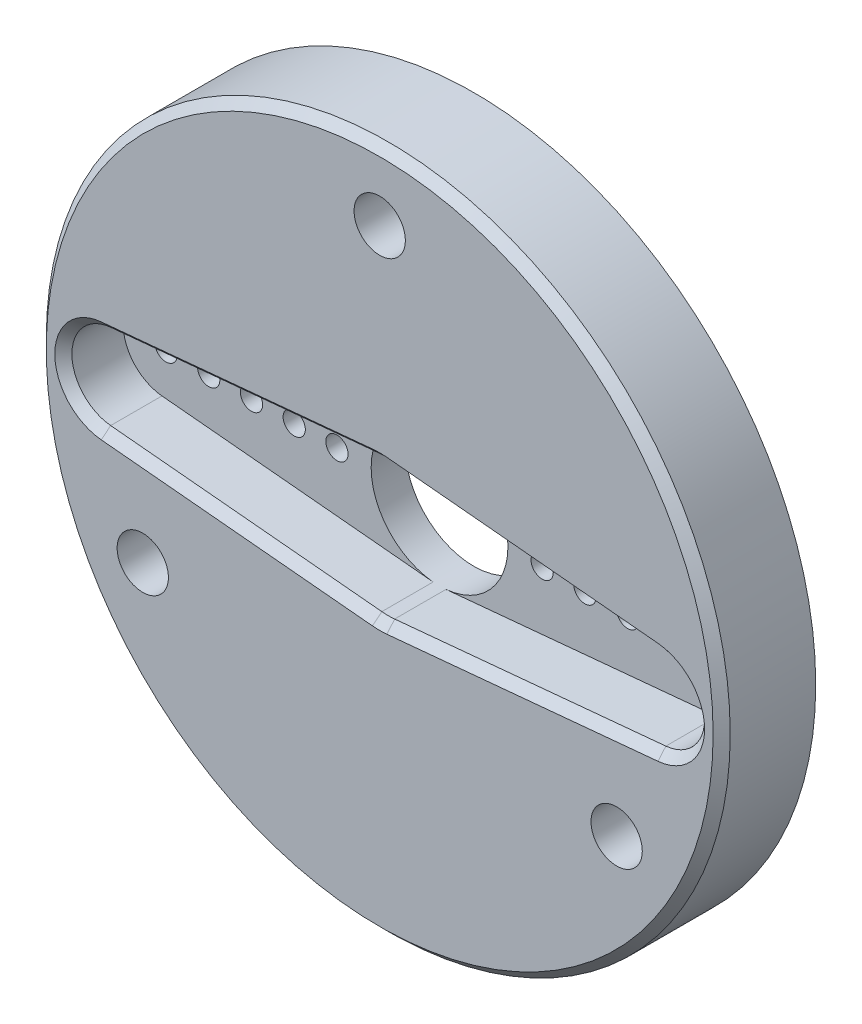
SolidWorks part; units mm, degrees
ref_plane "前视基准面" through (0, 0, 0) normal (0, 0, 1) x (1, 0, 0)
ref_plane "上视基准面" through (0, 0, 0) normal (0, 1, 0) x (1, 0, 0)
ref_plane "右视基准面" through (0, 0, 0) normal (1, 0, 0) x (0, 0, -1)
sketch "草图1" plane through (0, 0, 0) normal (0, 0, 1) x (1, 0, 0)
  line L0 (0, -3.025) -> (0, 3.025) construction
  circle A0 centre (0, 0) radius 20
  circle A1 centre (0, 0) radius 4
  circle A2 centre (6, 0) radius 0.65
  circle A3 centre (8.5, 0) radius 0.65
  circle A4 centre (11, 0) radius 0.65
  circle A5 centre (13.5, 0) radius 0.65
  circle A6 centre (16, 0) radius 0.65
  circle A7 centre (-16, 0) radius 0.65
  circle A8 centre (-13.5, 0) radius 0.65
  circle A9 centre (-11, 0) radius 0.65
  circle A10 centre (-8.5, 0) radius 0.65
  circle A11 centre (-6, 0) radius 0.65
  dimension "D1" = 40
  dimension "D2" = 8
  dimension "D4" = 1.3
  dimension "D3" = 6
  dimension "D6" = 10
  dimension "D5" = 5
extrude "凸台-拉伸1" add sketch "草图1" along normal blind 5.5
sketch "草图2" plane through (0, 0, 5.5) normal (0, 0, 1) x (1, 0, 0)
  line L0 (-16.2344, 2.489) -> (-0.375, 3.9824)
  line L1 (3.025, 0) -> (-3.025, 0) construction
  line L2 (-16.2344, -2.489) -> (-0.375, -3.9824)
  line L3 (0, -3.025) -> (0, 3.025) construction
  line L4 (16.2344, -2.489) -> (0.375, -3.9824)
  line L5 (16.2344, 2.489) -> (0.375, 3.9824)
  arc A0 (-16.2344, 2.489) -> (-16.2344, -2.489) centre (-16, 0) ccw
  circle A1 centre (0, 0) radius 4 construction
  arc A2 (-0.375, -3.9824) -> (0.375, -3.9824) centre (0, 0) ccw
  arc A3 (16.2344, 2.489) -> (16.2344, -2.489) centre (16, 0) cw
  arc A4 (0.375, 3.9824) -> (-0.375, 3.9824) centre (0, 0) ccw
  dimension "D1" = 5
extrude "切除-拉伸1" cut sketch "草图2" against normal blind 3.5
sketch "草图3" plane through (0, 0, 5.5) normal (0, 0, 1) x (1, 0, 0)
  circle A0 centre (0, 16) radius 1.5
  circle A1 centre (13.8564, -8) radius 1.5
  circle A2 centre (-13.8564, -8) radius 1.5
  dimension "D1" = 3
  dimension "D2" = 16
  dimension "D3" = 3
extrude "切除-拉伸2" cut sketch "草图3" against normal blind 13
chamfer "倒角1" distance 0.5 angle 45 1 edges at (20, 0, 5.5)
chamfer "倒角2" distance 0.5 angle 45 8 edges at (8.3047, -3.2357, 5.5) (18.5, 0, 5.5) (0, -4, 5.5) (8.3047, 3.2357, 5.5) (-8.3047, -3.2357, 5.5) (0, 4, 5.5) (-18.5, 0, 5.5) (-8.3047, 3.2357, 5.5)
